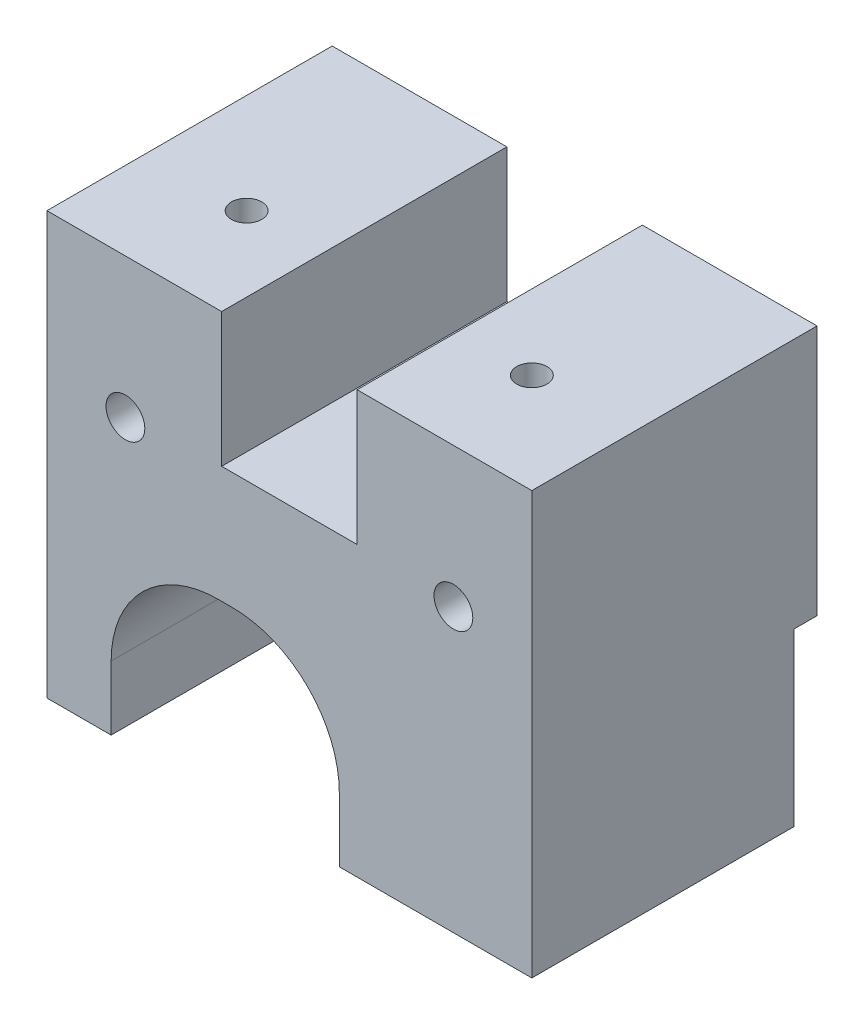
SolidWorks part; units mm, degrees
material "Nylon 6/10"
ref_plane "Front Plane" through (0, 0, 0) normal (0, 0, 1) x (1, 0, 0)
ref_plane "Top Plane" through (0, 0, 0) normal (0, 1, 0) x (1, 0, 0)
ref_plane "Right Plane" through (0, 0, 0) normal (1, 0, 0) x (0, 0, -1)
sketch "Sketch1" plane through (0, 0, 0) normal (0, 1, 0) x (1, 0, 0)
  line L1 (-21.59, -12.7) -> (21.59, -12.7)
  line L2 (-21.59, -12.7) -> (-21.59, 12.7)
  line L3 (-21.59, 12.7) -> (21.59, 12.7)
  line L4 (21.59, -12.7) -> (21.59, 12.7)
  line L5 (-21.59, -12.7) -> (21.59, 12.7) construction
  line L6 (-21.59, 12.7) -> (21.59, -12.7) construction
  point P0 (0, 0)
  dimension "D1" = 25.4
  dimension "D2" = 43.18
extrude "Base" add sketch "Sketch1" along normal blind 37.592
chamfer "SideChamfer" [suppressed] distance 12.7 angle 45
chamfer "BackChamfers" [suppressed] distance 6.35 angle 45
sketch "Sketch2" plane through (0, 0, 12.7) normal (0, 0, 1) x (1, 0, 0)
  line L1 (-6.0325, 37.592) -> (6.0325, 37.592)
  line L2 (-6.0325, 37.592) -> (-6.0325, 25.654)
  line L3 (-6.0325, 25.654) -> (6.0325, 25.654)
  line L4 (6.0325, 37.592) -> (6.0325, 25.654)
  line L5 (-6.0325, 37.592) -> (6.0325, 25.654) construction
  line L6 (-6.0325, 25.654) -> (6.0325, 37.592) construction
  line L7 (0, 25.654) -> (0, 37.592) construction
  line L8 (-21.59, 37.592) -> (21.59, 37.592) construction
  point P0 (0, 31.623)
  dimension "D1" = 11.938
  dimension "D2" = 12.065
extrude "LinActSlot" cut sketch "Sketch2" against normal through all
hole_wizard "MoutingHoles" positions "Sketch4" profile "Sketch3" tap size "#6-32" standard "ANSI Inch"
sketch "Sketch4" plane through (14.1604, 37.592, 8.3734) normal (0, -1, 0) x (-1, 0, 0)
  line L0 (14.1604, 8.3734) -> (14.1604, 11.4563) construction
  line L3 (35.7504, -4.3266) -> (20.1929, -4.3266) construction
  line L4 (8.1279, -4.3266) -> (-7.4296, -4.3266) construction
  point P0 (1.4604, 4.5634)
  point P2 (26.8604, 4.5634)
  dimension "D1" = 12.7
  dimension "D2" = 8.89
  dimension "D3" = 12.7
  dimension "D4" = 8.89
sketch "Sketch3" plane through (12.7, 37.592, 3.81) normal (1, 0, 0) x (0, 0, 1)
  line L0 (0, 0) -> (0, 15.2907)
  line L1 (0, 15.2907) -> (1.3525, 14.478)
  line L2 (1.3525, 14.478) -> (1.3525, 0)
  line L5 (1.3525, 0) -> (0, 0)
  line L10 (0, 15.2907) -> (-1.3526, 14.478) construction
  line L11 (0, -6.35) -> (0, 107.95) construction
  dimension "Tap Drill Dia." = 2.7051
  dimension "Tap Drill Depth" = 14.478
  dimension "Drill Angle" = 118
sketch "Sketch11" plane through (0, 0, -12.7) normal (0, 0, -1) x (-1, 0, 0)
  line L0 (-21.59, 0) -> (21.59, 0) construction
  line L1 (15.875, 5.08) -> (15.875, 5.715)
  line L2 (6.35, 15.24) -> (5.08, 15.24)
  line L3 (21.59, 37.592) -> (21.59, 0) construction
  line L4 (15.875, 5.08) -> (15.875, 0)
  line L5 (-21.59, 0) -> (21.59, 0) construction
  line L6 (15.875, 0) -> (-4.445, 0)
  line L7 (-4.445, 0) -> (-4.445, 5.08)
  line L8 (-4.445, 5.715) -> (-4.445, 5.08)
  arc A0 (15.875, 5.08) -> (-4.445, 5.08) centre (5.715, 5.08) ccw construction
  arc A1 (-4.445, 5.715) -> (5.08, 15.24) centre (5.08, 5.715) cw
  arc A2 (6.35, 15.24) -> (15.875, 5.715) centre (6.35, 5.715) cw
  dimension "D1" = 20.32
  dimension "D4" = 9.525
  dimension "D2" = 5.08
  dimension "D3" = 15.875
extrude "MotorSlot" cut sketch "Sketch11" against normal through all
hole_wizard "MotorMountingHoles2" positions "Sketch13" profile "Sketch12" tap size "#4-40" standard "ANSI Inch"
sketch "Sketch13" plane through (0, 0, -12.7) normal (0, 0, -1) x (-1, 0, 0)
  line L7 (6.35, 15.24) -> (5.08, 15.24) construction
  line L8 (6.35, 15.24) -> (5.08, 15.24) construction
  line L9 (5.715, 15.24) -> (5.715, -3.6836) construction
  arc A2 (15.875, 5.715) -> (6.35, 15.24) centre (6.35, 5.715) ccw construction
  arc A3 (15.875, 5.715) -> (6.35, 15.24) centre (6.35, 5.715) ccw construction
  point P0 (18.215, 5.715)
  point P2 (-6.785, 5.715)
  dimension "D1" = 25
sketch "Sketch12" plane through (-18.215, 5.715, -12.7) normal (1, 0, 0) x (0, 1, 0)
  line L0 (0, 0) -> (0, 12.1092)
  line L1 (0, 12.1092) -> (1.1303, 11.43)
  line L2 (1.1303, 11.43) -> (1.1303, 0)
  line L5 (1.1303, 0) -> (0, 0)
  line L10 (0, 12.1092) -> (-1.1303, 11.43) construction
  line L11 (0, -6.35) -> (0, 107.95) construction
  dimension "Tap Drill Dia." = 2.2606
  dimension "Tap Drill Depth" = 11.43
  dimension "Drill Angle" = 118
cosmetic thread "Hole Thread4" parameters "D1"=9.398, "D2"=2.8448
cosmetic thread "Hole Thread5" parameters "D1"=9.398, "D2"=2.8448
hole_wizard "GripperSetScrew" [suppressed] positions "Sketch15" profile "Sketch14" tap size "#4-40" standard "ANSI Inch"
sketch "Sketch15" plane through (0, 18.542, 0) normal (0, 1, 0) x (1, 0, 0)
  line L0 (0, 0) -> (0, -19.304) construction
  line L1 (-6.0325, -19.304) -> (6.0325, -19.304) construction
  point P0 (0, -12.954)
  dimension "D1" = 6.35
sketch "Sketch14" plane through (0, 18.542, 12.954) normal (1, 0, 0) x (0, 0, 1)
  line L0 (0, 0) -> (0, 18.542)
  line L1 (0, 18.542) -> (1.1303, 18.542)
  line L2 (1.1303, 18.542) -> (1.1303, 0)
  line L5 (1.1303, 0) -> (0, 0)
  line L11 (0, -6.35) -> (0, 107.95) construction
  dimension "Thru Tap Drill Dia." = 2.2606
  dimension "Thru Tap Drill Depth" = 18.542
cosmetic thread "Hole Thread6" [suppressed] parameters "D2"=2.8448
hole_wizard "#8-32 Tapped Hole1" positions "Sketch22" profile "Sketch21" tap size "#8-32" standard "ANSI Inch"
sketch "Sketch22" plane through (0, 0, 12.7) normal (0, 0, 1) x (1, 0, 0)
  line L0 (-21.5692, 25.146) -> (16.258, 25.146) construction
  line L1 (0, 25.654) -> (0, 0) construction
  line L2 (-6.0325, 25.654) -> (6.0325, 25.654) construction
  line L6 (6.0325, 37.592) -> (21.59, 37.592) construction
  point P0 (-14.605, 25.146)
  point P2 (14.605, 25.146)
  dimension "D1" = 29.21
  dimension "D2" = 12.446
sketch "Sketch21" plane through (-14.605, 25.146, 12.7) normal (1, 0, 0) x (0, -1, 0)
  line L0 (0, 0) -> (0, 8.6578)
  line L1 (0, 8.6578) -> (1.7272, 7.62)
  line L2 (1.7272, 7.62) -> (1.7272, 0)
  line L5 (1.7272, 0) -> (0, 0)
  line L10 (0, 8.6578) -> (-1.7272, 7.62) construction
  line L11 (0, -6.35) -> (0, 107.95) construction
  dimension "Tap Drill Dia." = 3.4544
  dimension "Tap Drill Depth" = 7.62
  dimension "Drill Angle" = 118
sketch "Sketch23" plane through (0, 0, -12.7) normal (0, 0, -1) x (-1, 0, 0)
  line L0 (-21.59, 37.592) -> (-21.59, 0) construction
  line L1 (21.59, 0) -> (-21.59, 0)
  line L2 (21.59, 0) -> (21.59, 15.24)
  line L4 (21.59, 15.24) -> (-21.59, 15.24)
  line L5 (-21.59, 0) -> (-21.59, 15.24)
  circle A0 centre (18.215, 5.715) radius 1.1303 construction
  dimension "D1" = 9.525
extrude "Cut-Extrude1" cut sketch "Sketch23" against normal blind 2.032
